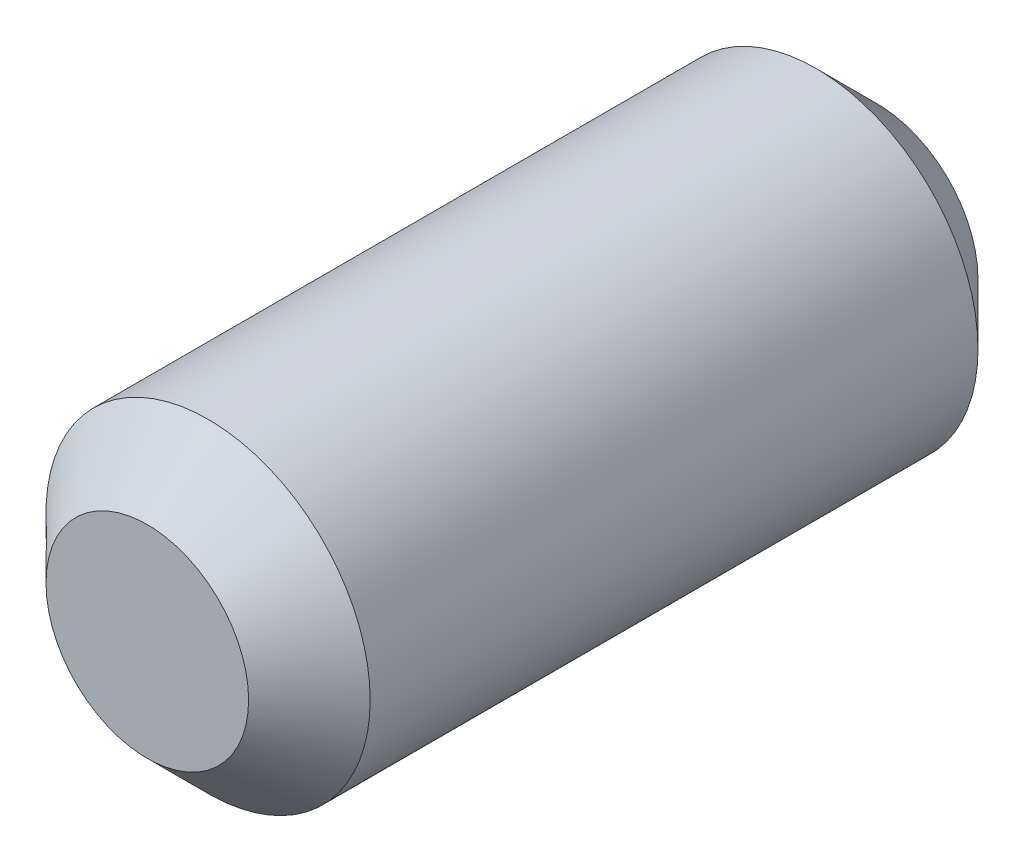
SolidWorks part; units mm, degrees
ref_plane "Спереди" through (0, 0, 0) normal (0, 0, 1) x (1, 0, 0)
ref_plane "Сверху" through (0, 0, 0) normal (0, 1, 0) x (1, 0, 0)
ref_plane "Справа" through (0, 0, 0) normal (1, 0, 0) x (0, 0, -1)
sketch "Эскиз1" plane through (0, 0, 0) normal (0, 0, 1) x (1, 0, 0)
  circle A0 centre (0, 0) radius 4
  dimension "D1" = 8
extrude "Вытянуть1" add sketch "Эскиз1" along normal blind 18
chamfer "Фаска1" distance 1.5 angle 45
